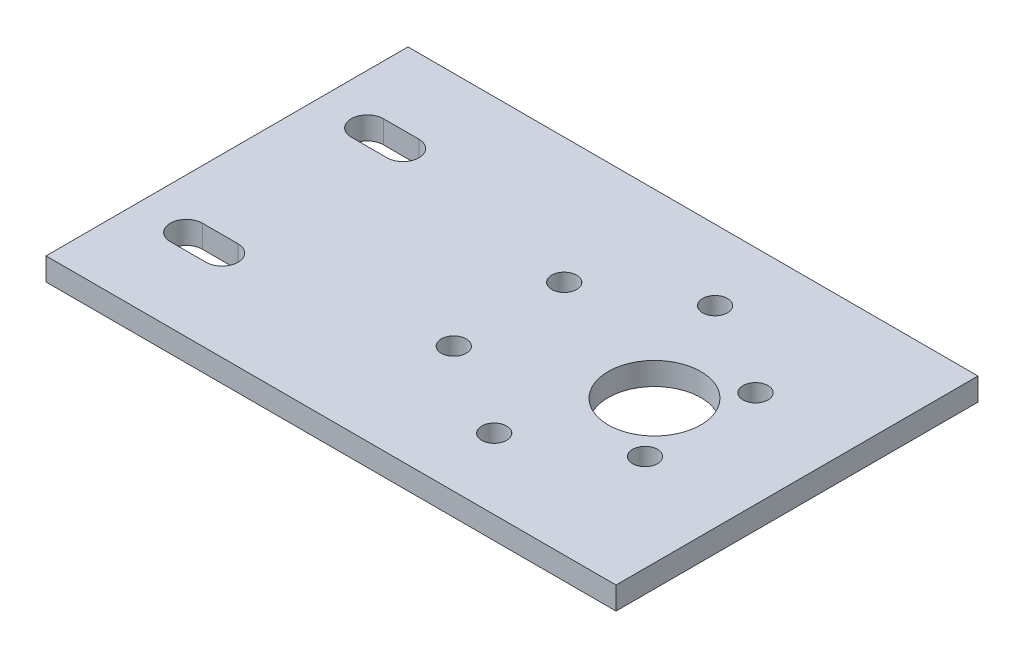
SolidWorks part; units mm, degrees
ref_plane "Front Plane" through (0, 0, 0) normal (0, 0, 1) x (1, 0, 0)
ref_plane "Top Plane" through (0, 0, 0) normal (0, 1, 0) x (1, 0, 0)
ref_plane "Right Plane" through (0, 0, 0) normal (1, 0, 0) x (0, 0, -1)
sketch "Sketch1" plane through (0, 0, 0) normal (0, 1, 0) x (1, 0, 0)
  line L0 (22.55, 38.1) -> (102.55, 38.1)
  line L1 (102.55, 0) -> (22.55, 0)
  line L4 (102.55, 0) -> (102.55, 38.1)
  line L5 (29.55, 29.5) -> (34.55, 29.5)
  line L6 (22.55, 38.1) -> (22.55, 0)
  line L7 (29.55, 4.1) -> (34.55, 4.1)
  line L8 (29.55, 34) -> (34.55, 34)
  line L9 (29.55, 8.6) -> (34.55, 8.6)
  circle A0 centre (82.55, 19.05) radius 6.5
  circle A1 centre (75.55, 34.55) radius 1.75
  circle A2 centre (88.9734, 26.8) radius 1.75
  circle A3 centre (88.9734, 11.3) radius 1.75
  circle A4 centre (75.55, 3.55) radius 1.75
  arc A5 (34.55, 29.5) -> (34.55, 34) centre (34.55, 31.75) ccw
  arc A6 (29.55, 34) -> (29.55, 29.5) centre (29.55, 31.75) ccw
  arc A7 (29.55, 8.6) -> (29.55, 4.1) centre (29.55, 6.35) ccw
  arc A8 (34.55, 4.1) -> (34.55, 8.6) centre (34.55, 6.35) ccw
  circle A9 centre (62.1266, 11.3) radius 1.75
  circle A10 centre (62.1266, 26.8) radius 1.75
  point P12 (75.55, 19.05)
  point P18 (82.55, 19.05)
  point P30 (82.55, 19.05)
  point P33 (75.55, 19.05)
  dimension "D1" = 13
  dimension "D4" = 15.5
  dimension "D5" = 7
  dimension "D8" = 38.1
  dimension "D13" = 53
  dimension "D6" = 5
  dimension "D3" = 2.25
  dimension "D2" = 20
  dimension "D7" = 7
  dimension "D9" = 6
  dimension "D10" = 19.05
extrude "Boss-Extrude1" add sketch "Sketch1" along normal blind 3.175
sketch "Sketch2" plane through (0, 3.175, 0) normal (0, 1, 0) x (1, 0, 0)
  line L1 (22.55, 38.1) -> (102.55, 38.1)
  line L2 (22.55, 38.1) -> (22.55, 44.45)
  line L3 (22.55, 44.45) -> (102.55, 44.45)
  line L4 (102.55, 38.1) -> (102.55, 44.45)
  line L5 (102.55, 0) -> (22.55, 0)
  line L6 (102.55, 0) -> (102.55, -6.35)
  line L7 (102.55, -6.35) -> (22.55, -6.35)
  line L8 (22.55, 0) -> (22.55, -6.35)
extrude "Boss-Extrude2" add sketch "Sketch2" against normal blind 3.175
